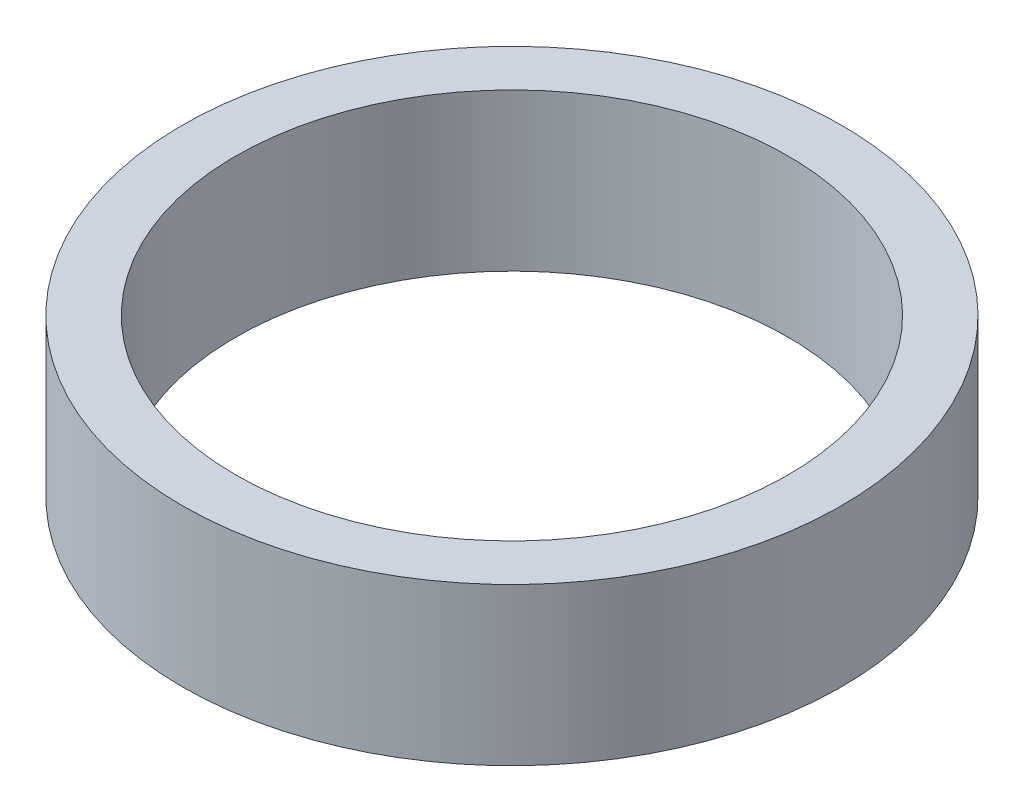
SolidWorks part; units mm, degrees
material "丙烯酸(中高冲击)"
ref_plane "前视基准面" through (0, 0, 0) normal (0, 0, 1) x (1, 0, 0)
ref_plane "上视基准面" through (0, 0, 0) normal (0, 1, 0) x (1, 0, 0)
ref_plane "右视基准面" through (0, 0, 0) normal (1, 0, 0) x (0, 0, -1)
sketch "草图1" plane through (0, 0, 0) normal (0, 1, 0) x (1, 0, 0)
  circle A0 centre (0, 0) radius 52.5
  circle A1 centre (0, 0) radius 11.15
  dimension "D1" = 105
  dimension "D2" = 22.3
extrude "凸台-拉伸1" add sketch "草图1" along normal blind 25
sketch "草图2" plane through (0, 25, 0) normal (0, 1, 0) x (1, 0, 0)
  line L0 (-34.5, 0) -> (-21.15, 0)
  line L1 (-34.5, -5) -> (-21.15, -5)
  line L2 (-34.5, 5) -> (-21.15, 5)
  line L3 (-21.15, 5) -> (-20.5505, 5)
  line L4 (-21.15, -5) -> (-20.5505, -5)
  line L5 (-12.9199, 32.3779) -> (-6.2449, 20.8164)
  line L6 (-6.2449, 20.8164) -> (-5.9451, 20.2972)
  line L7 (-21.5801, 27.3779) -> (-14.9051, 15.8164)
  line L8 (-14.9051, 15.8164) -> (-14.6054, 15.2972)
  line L9 (21.5801, 27.3779) -> (14.9051, 15.8164)
  line L10 (14.9051, 15.8164) -> (14.6054, 15.2972)
  line L11 (12.9199, 32.3779) -> (6.2449, 20.8164)
  line L12 (6.2449, 20.8164) -> (5.9451, 20.2972)
  line L13 (34.5, -5) -> (21.15, -5)
  line L14 (21.15, -5) -> (20.5505, -5)
  line L15 (34.5, 5) -> (21.15, 5)
  line L16 (21.15, 5) -> (20.5505, 5)
  line L17 (12.9199, -32.3779) -> (6.2449, -20.8164)
  line L18 (6.2449, -20.8164) -> (5.9451, -20.2972)
  line L19 (21.5801, -27.3779) -> (14.9051, -15.8164)
  line L20 (14.9051, -15.8164) -> (14.6054, -15.2972)
  line L21 (-21.5801, -27.3779) -> (-14.9051, -15.8164)
  line L22 (-14.9051, -15.8164) -> (-14.6054, -15.2972)
  line L23 (-12.9199, -32.3779) -> (-6.2449, -20.8164)
  line L24 (-6.2449, -20.8164) -> (-5.9451, -20.2972)
  circle A0 centre (0, 0) radius 21.15
  circle A1 centre (0, 0) radius 34.5
  circle A2 centre (0, 0) radius 52.5 construction
  circle A3 centre (0, 0) radius 11.15 construction
  dimension "D1" = 18
  dimension "D2" = 10
  dimension "D3" = 5
  dimension "D5" = 6
  dimension "D4" = 5
extrude "切除-拉伸1" cut sketch "草图2" against normal blind 30 contours L7 A1 L2 L3 A0 L8
pattern_circular "阵列(圆周)1" count 6 over 360 about axis through (0, 25, 0) along (0, -1, 0) of "切除-拉伸1"
fillet "圆角1" radius 5 24 edges at (-21.398, 12.5, -27.0624) (-14.6054, 12.5, -15.2972) (-20.5505, 12.5, -5) (-34.1358, 12.5, -5) (-34.1358, 12.5, 5) (-20.5505, 12.5, 5) (-14.6054, 12.5, 15.2972) (-21.398, 12.5, 27.0624) (-12.7378, 12.5, 32.0624) (-5.9451, 12.5, 20.2972) (5.9451, 12.5, 20.2972) (12.7378, 12.5, 32.0624) (21.398, 12.5, 27.0624) (14.6054, 12.5, 15.2972) (20.5505, 12.5, 5) (34.1358, 12.5, 5) (34.1358, 12.5, -5) (20.5505, 12.5, -5) (14.6054, 12.5, -15.2972) (21.398, 12.5, -27.0624) (12.7378, 12.5, -32.0624) (5.9451, 12.5, -20.2972) (-5.9451, 12.5, -20.2972) (-12.7378, 12.5, -32.0624)
sketch "草图3" plane through (0, 25, 0) normal (0, 1, 0) x (1, 0, 0)
  circle A0 centre (0, 0) radius 44
  arc M4 (-32.4573, 11.6949) -> (-26.3568, 22.2614) centre (0, 0) cw
  arc M5 (-26.3568, 22.2614) -> (-18.2068, 21.5351) centre (-22.5369, 19.0351) cw
  line M6 (-18.2068, 21.5351) -> (-16.4113, 18.4253)
  arc M7 (-16.4113, 18.4253) -> (-16.7756, 12.8803) centre (-20.7415, 15.9253) cw
  arc M8 (-16.7756, 12.8803) -> (-19.5425, 8.088) centre (0, 0) ccw
  arc M9 (-19.5425, 8.088) -> (-24.1624, 5) centre (-24.1624, 10) cw
  line M10 (-24.1624, 5) -> (-27.7534, 5)
  arc M11 (-27.7534, 5) -> (-32.4573, 11.6949) centre (-27.7534, 10) cw
  arc M12 (-6.1006, 33.9563) -> (6.1006, 33.9563) centre (0, 0) cw
  arc M13 (6.1006, 33.9563) -> (9.5466, 26.5351) centre (5.2164, 29.0351) cw
  line M14 (9.5466, 26.5351) -> (7.7511, 23.4253)
  arc M15 (7.7511, 23.4253) -> (2.7669, 20.9682) centre (3.421, 25.9253) cw
  arc M16 (2.7669, 20.9682) -> (-2.7669, 20.9682) centre (0, 0) ccw
  arc M17 (-2.7669, 20.9682) -> (-7.7511, 23.4253) centre (-3.421, 25.9253) cw
  line M18 (-7.7511, 23.4253) -> (-9.5466, 26.5351)
  arc M19 (-9.5466, 26.5351) -> (-6.1006, 33.9563) centre (-5.2164, 29.0351) cw
  arc M20 (6.1006, -33.9563) -> (-6.1006, -33.9563) centre (0, 0) cw
  arc M21 (-6.1006, -33.9563) -> (-9.5466, -26.5351) centre (-5.2164, -29.0351) cw
  line M22 (-9.5466, -26.5351) -> (-7.7511, -23.4253)
  arc M23 (-7.7511, -23.4253) -> (-2.7669, -20.9682) centre (-3.421, -25.9253) cw
  arc M24 (-2.7669, -20.9682) -> (2.7669, -20.9682) centre (0, 0) ccw
  arc M25 (2.7669, -20.9682) -> (7.7511, -23.4253) centre (3.421, -25.9253) cw
  line M26 (7.7511, -23.4253) -> (9.5466, -26.5351)
  arc M27 (9.5466, -26.5351) -> (6.1006, -33.9563) centre (5.2164, -29.0351) cw
  arc M28 (-26.3568, -22.2614) -> (-32.4573, -11.6949) centre (0, 0) cw
  arc M29 (-32.4573, -11.6949) -> (-27.7534, -5) centre (-27.7534, -10) cw
  line M30 (-27.7534, -5) -> (-24.1624, -5)
  arc M35 (-18.2068, -21.5351) -> (-26.3568, -22.2614) centre (-22.5369, -19.0351) cw
  arc M36 (32.4573, -11.6949) -> (26.3568, -22.2614) centre (0, 0) cw
  arc M37 (26.3568, -22.2614) -> (18.2068, -21.5351) centre (22.5369, -19.0351) cw
  line M38 (18.2068, -21.5351) -> (16.4113, -18.4253)
  arc M39 (16.4113, -18.4253) -> (16.7756, -12.8803) centre (20.7415, -15.9253) cw
  arc M40 (16.7756, -12.8803) -> (19.5425, -8.088) centre (0, 0) ccw
  arc M41 (19.5425, -8.088) -> (24.1624, -5) centre (24.1624, -10) cw
  line M42 (24.1624, -5) -> (27.7534, -5)
  arc M43 (27.7534, -5) -> (32.4573, -11.6949) centre (27.7534, -10) cw
  arc M44 (26.3568, 22.2614) -> (32.4573, 11.6949) centre (0, 0) cw
  arc M45 (32.4573, 11.6949) -> (27.7534, 5) centre (27.7534, 10) cw
  line M46 (27.7534, 5) -> (24.1624, 5)
  arc M47 (24.1624, 5) -> (19.5425, 8.088) centre (24.1624, 10) cw
  arc M48 (19.5425, 8.088) -> (16.7756, 12.8803) centre (0, 0) ccw
  arc M49 (16.7756, 12.8803) -> (16.4113, 18.4253) centre (20.7415, 15.9253) cw
  line M50 (16.4113, 18.4253) -> (18.2068, 21.5351)
  arc M51 (18.2068, 21.5351) -> (26.3568, 22.2614) centre (22.5369, 19.0351) cw
  dimension "D1" = 88
extrude "切除-拉伸2" cut sketch "草图3" against normal blind 30 contours A0 M11 M4 M5 M6 M7 M8 M9 M10 M19 M12 M13 M14 M15 M16 M17 M18 M51 M44 M45 M46 M47 M48 M49 M50 M43 M36 M37 M38 M39 M40 M41 M42 M27 M20 M21 M22 M23 M24 M25 M26 M35 M28 M29 M30
